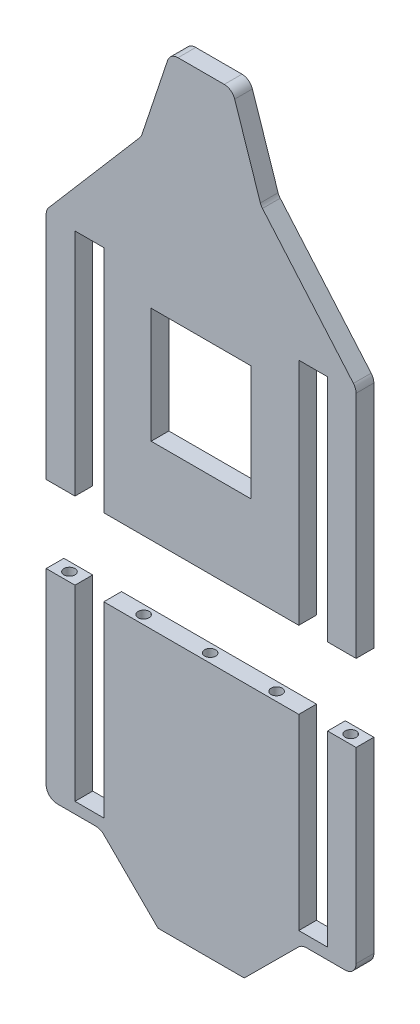
SolidWorks part; units mm, degrees
ref_plane "Front Plane" through (0, 0, 0) normal (0, 0, 1) x (1, 0, 0)
ref_plane "Top Plane" through (0, 0, 0) normal (0, 1, 0) x (1, 0, 0)
ref_plane "Right Plane" through (0, 0, 0) normal (1, 0, 0) x (0, 0, -1)
sketch "Sketch1" plane through (0, 0, 0) normal (0, 0, 1) x (1, 0, 0)
  line L0 (0, 30.8599) -> (0, 219.0089)
  line L1 (25.9628, 24.405) -> (50.5, 0)
  line L2 (59.5039, 309.9858) -> (80.3789, 309.9858)
  line L3 (134.8829, 25.8599) -> (117.446, 25.8599)
  line L5 (5, 25.8599) -> (22.4368, 25.8599)
  line L6 (96.9829, 270.8599) -> (83.9829, 270.8599) construction
  line L7 (0, 220.8599) -> (3.9, 220.8599) construction
  line L8 (3.9, 220.8599) -> (42.9, 220.8599) construction
  line L9 (42.9, 220.8599) -> (42.9, 270.8599) construction
  line L10 (96.9829, 220.8599) -> (96.9829, 270.8599) construction
  line L11 (115.3829, 25.8599) -> (89.3829, 25.8599) construction
  line L12 (24.5, 25.8599) -> (50.5, 25.8599) construction
  line L13 (0, 0) -> (0, 25.8599) construction
  line L14 (42.9, 270.8599) -> (55.9, 270.8599) construction
  line L15 (55.9, 270.8599) -> (55.9, 310) construction
  line L16 (54.8024, 306.5671) -> (43.2101, 271.7903)
  line L17 (42.2614, 270.1156) -> (1.2053, 222.2648)
  line L18 (50.5, 25.8599) -> (50.5, 0) construction
  line L20 (135.9829, 220.8599) -> (96.9829, 220.8599) construction
  line L21 (139.8829, 220.8599) -> (135.9829, 220.8599) construction
  line L22 (97.6215, 270.1156) -> (138.6775, 222.2648)
  line L23 (85.0805, 306.5671) -> (96.6727, 271.7903)
  line L24 (139.8829, 30.8599) -> (139.8829, 219.0089)
  line L25 (89.3829, 25.8599) -> (89.3829, 0) construction
  line L26 (113.92, 24.405) -> (89.3829, 0)
  line L27 (89.3829, 0) -> (50.5, 0)
  line L28 (0, 219.0089) -> (13, 219.0089) construction
  line L29 (13, 219.0089) -> (13, 30.8599)
  line L30 (13, 30.8599) -> (26, 30.8599)
  line L31 (26, 30.8599) -> (26, 219.0089)
  line L32 (26, 219.0089) -> (13, 219.0089)
  line L35 (127, 30.8599) -> (114, 30.8599)
  line L36 (114, 219.0089) -> (127, 219.0089)
  line L37 (114, 30.8599) -> (114, 219.0089)
  line L38 (127, 219.0089) -> (127, 30.8599)
  arc A0 (54.8024, 306.5671) -> (59.5039, 309.9858) centre (59.5458, 304.986) cw
  arc A1 (42.2614, 270.1156) -> (43.2101, 271.7903) centre (38.4667, 273.3715) ccw
  arc A2 (0, 219.0089) -> (1.2053, 222.2648) centre (5, 219.0089) cw
  arc A3 (85.0805, 306.5671) -> (80.3789, 309.9858) centre (80.337, 304.986) ccw
  arc A4 (139.8829, 219.0089) -> (138.6775, 222.2648) centre (134.8829, 219.0089) ccw
  arc A5 (97.6215, 270.1156) -> (96.6727, 271.7903) centre (101.4161, 273.3715) cw
  arc A6 (117.446, 25.8599) -> (113.92, 24.405) centre (117.446, 20.8599) ccw
  arc A7 (22.4368, 25.8599) -> (25.9628, 24.405) centre (22.4368, 20.8599) cw
  arc A8 (134.8829, 25.8599) -> (139.8829, 30.8599) centre (134.8829, 30.8599) ccw
  arc A9 (5, 25.8599) -> (0, 30.8599) centre (5, 30.8599) cw
  dimension "D1" = 5
  dimension "D2" = 5
  dimension "D3" = 5
extrude "Boss-Extrude1" add sketch "Sketch1" along normal blind 8
sketch "Sketch2" plane through (0, 0, 8) normal (0, 0, 1) x (1, 0, 0)
  line L2 (92.3829, 206.0089) -> (47.3829, 206.0089)
  line L3 (26, 219.0089) -> (26, 206.0089)
  line L4 (26, 30.8599) -> (26, 219.0089) construction
  line L8 (47.3829, 206.0089) -> (47.3829, 154.0089)
  line L9 (47.3829, 154.0089) -> (92.3829, 154.0089)
  line L10 (92.3829, 206.0089) -> (92.3829, 154.0089)
extrude "Cut-Extrude1" cut sketch "Sketch2" against normal through all contours L10 L2 L8 L9
sketch "Sketch3" plane through (0, 0, 0) normal (0, 0, -1) x (-1, 0, 0)
  line L1 (0, 115.3599) -> (-139.8829, 115.3599)
  line L2 (-139.8829, 30.8599) -> (-139.8829, 219.0089) construction
split "Split1" trim tools "Sketch3" bodies to split 102 resulting bodies 103 104
move or copy body "Body-Move/Copy1" bodies to move or copy 103 copy no translate (0, 34.7934, 0) parameters "D1"=0, "D2"=34.7934, "D3"=0
sketch "Sketch4" plane through (0, 150.1534, 0) normal (0, -1, 0) x (-1, 0, 0)
  circle A0 centre (-6.5, -4) radius 2.5
  circle A1 centre (-70, -4) radius 2.5
  circle A2 centre (-40, -4) radius 2.5
  circle A3 centre (-100, -4) radius 2.5
  circle A4 centre (-133.4414, -4) radius 2.5
sketch "Sketch5" plane through (0, 115.3599, -115.3599) normal (0, -1, 0) x (1, 0, 0)
  circle A0 centre (133.4414, 119.3599) radius 2.5
  circle A1 centre (70, 119.3599) radius 2.5
  circle A2 centre (100, 119.3599) radius 2.5
  circle A3 centre (40, 119.3599) radius 2.5
  circle A4 centre (6.5, 119.3599) radius 2.5
  point P10 (0, 0)
  point P11 (6.5, 119.3599)
  point P13 (40, 119.3599)
  point P15 (70, 119.3599)
  point P17 (100, 119.3599)
  point P19 (133.4414, 119.3599)
extrude "Cut-Extrude6" cut sketch "Sketch5" along normal blind 5.2
extrude "Cut-Extrude7" cut sketch "Sketch4" against normal blind 5.2
